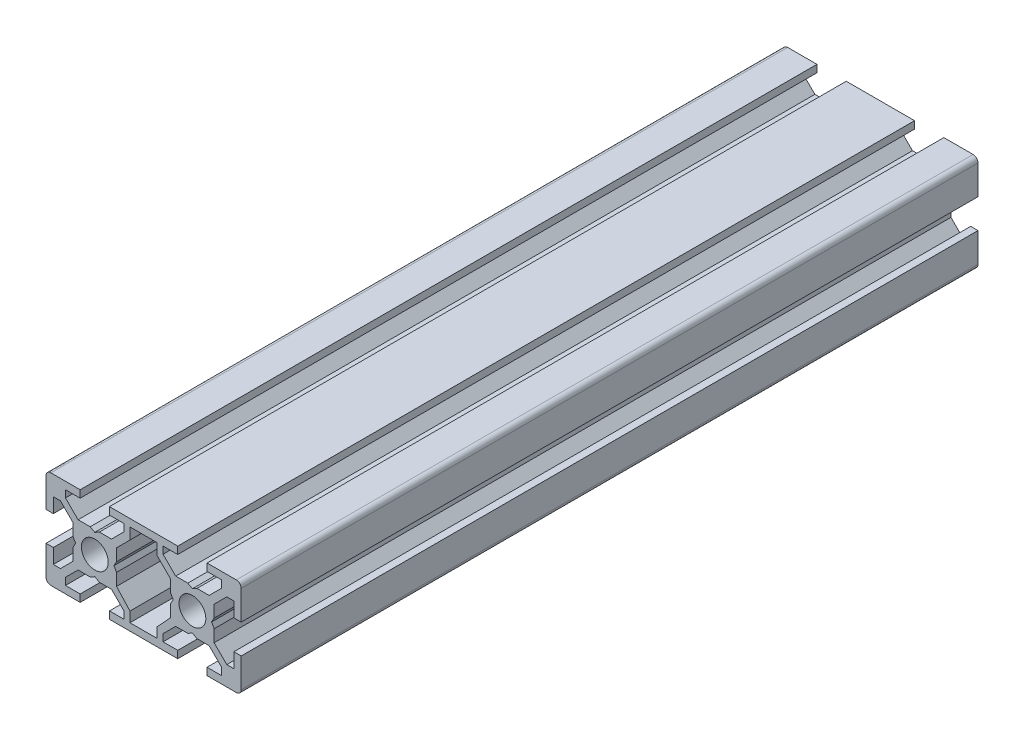
SolidWorks part; units mm, degrees
ref_plane "Front Plane" through (0, 0, 0) normal (0, 0, 1) x (1, 0, 0)
ref_plane "Top Plane" through (0, 0, 0) normal (0, 1, 0) x (1, 0, 0)
ref_plane "Right Plane" through (0, 0, 0) normal (1, 0, 0) x (0, 0, -1)
sketch "Sketch1" plane through (0, 0, 0) normal (0, 0, 1) x (1, 0, 0)
  line L0 (-707.1068, -707.1068) -> (34648.2323, 34648.2323) construction
  line L1 (-3.0018, 10) -> (-10, 10)
  line L2 (0.9376, 4.4579) -> (-0.0011, 3.9339)
  line L3 (3.4252, 4.4579) -> (0.9376, 4.4579)
  line L4 (6.0128, 7.0454) -> (3.4252, 4.4579)
  line L5 (0, -1000) -> (0, 49000) construction
  line L6 (-1000, 0) -> (49000, 0) construction
  line L7 (6.0128, 8.5) -> (6.0128, 7.0454)
  line L8 (3.0018, 8.5) -> (6.0128, 8.5)
  line L9 (3.0018, 10) -> (16.9982, 10)
  line L10 (3.0018, 8.5) -> (3.0018, 10)
  line L11 (-707.1068, 707.1068) -> (34648.2323, -34648.2323) construction
  line L12 (-7.0458, 6.0144) -> (-4.4582, 3.4268)
  line L13 (-8.5008, 6.0144) -> (-7.0458, 6.0144)
  line L14 (-8.5008, 3.0018) -> (-8.5008, 6.0144)
  line L15 (0, -0.0423) -> (0.0002, 2.0704) construction
  line L16 (-10, 3.0018) -> (-10, 10)
  line L17 (-8.5008, 3.0018) -> (-10, 3.0018)
  line L18 (7.2087, -6.4198) -> (7.2087, -8.5)
  line L19 (7.2087, -8.5) -> (12.7913, -8.5)
  line L20 (7.2087, 6.1776) -> (7.2087, 8.5)
  line L21 (7.2087, 8.5) -> (12.7913, 8.5)
  line L22 (7.2087, 6.1776) -> (4.4583, 3.4262)
  line L23 (-3.0018, 8.5) -> (-3.0018, 10)
  line L24 (-3.0018, 8.5) -> (-6.0148, 8.5)
  line L25 (-6.0148, 8.5) -> (-6.0148, 7.0458)
  line L26 (-6.0148, 7.0458) -> (-3.4272, 4.4582)
  line L27 (-3.4272, 4.4582) -> (-0.9396, 4.4582)
  line L28 (-0.9396, 4.4582) -> (-0.0011, 3.9339)
  line L29 (-4.4582, 3.4268) -> (-4.4582, 0.9396)
  line L30 (-4.4582, 0.9396) -> (-3.9347, 0)
  line L31 (4.4575, 0.9396) -> (3.9347, 0)
  line L32 (4.4583, 3.4262) -> (4.4575, 0.9396)
  line L33 (10, -990) -> (10, 49010) construction
  line L34 (19.0624, -4.4579) -> (20.0011, -3.9339)
  line L35 (16.5748, -4.4579) -> (19.0624, -4.4579)
  line L36 (13.9872, -7.0454) -> (16.5748, -4.4579)
  line L37 (-0.9396, -4.4582) -> (-0.0011, -3.9339)
  line L38 (13.9872, -8.5) -> (13.9872, -7.0454)
  line L39 (16.9982, -8.5) -> (13.9872, -8.5)
  line L40 (16.9982, -8.5) -> (16.9982, -10)
  line L41 (24.4575, -0.9396) -> (23.9347, 0)
  line L42 (24.4582, -3.4268) -> (24.4575, -0.9396)
  line L43 (27.0458, -6.0144) -> (24.4582, -3.4268)
  line L44 (28.5008, -6.0144) -> (27.0458, -6.0144)
  line L45 (-3.4272, -4.4582) -> (-0.9396, -4.4582)
  line L46 (-6.0148, -7.0458) -> (-3.4272, -4.4582)
  line L47 (-6.0148, -8.5) -> (-6.0148, -7.0458)
  line L48 (-3.0018, -8.5) -> (-6.0148, -8.5)
  line L49 (-3.0018, -10) -> (-10, -10)
  line L50 (-3.0018, -8.5) -> (-3.0018, -10)
  line L51 (4.4588, -0.9386) -> (3.9347, 0)
  line L52 (4.4583, -3.4262) -> (4.4588, -0.9386)
  line L53 (7.2087, -6.4198) -> (4.4583, -3.4262)
  line L54 (28.5008, -3.0018) -> (28.5008, -6.0144)
  line L55 (30, -3.0018) -> (30, -10)
  line L56 (28.5008, -3.0018) -> (30, -3.0018)
  line L57 (12.7913, -6.4198) -> (15.5417, -3.4262)
  line L58 (-8.5008, -3.0018) -> (-10, -3.0018)
  line L59 (-10, -3.0018) -> (-10, -10)
  line L60 (-8.5008, -3.0018) -> (-8.5008, -6.0144)
  line L61 (-8.5008, -6.0144) -> (-7.0458, -6.0144)
  line L62 (-7.0458, -6.0144) -> (-4.4582, -3.4268)
  line L63 (-4.4582, -3.4268) -> (-4.4575, -0.9396)
  line L64 (-4.4575, -0.9396) -> (-3.9347, 0)
  line L65 (3.0018, -8.5) -> (3.0018, -10)
  line L66 (3.0018, -10) -> (16.9982, -10)
  line L67 (3.0018, -8.5) -> (6.0128, -8.5)
  line L68 (6.0128, -8.5) -> (6.0128, -7.0454)
  line L69 (6.0128, -7.0454) -> (3.4252, -4.4579)
  line L70 (3.4252, -4.4579) -> (0.9376, -4.4579)
  line L71 (0.9376, -4.4579) -> (-0.0011, -3.9339)
  line L72 (15.5417, -3.4262) -> (15.5412, -0.9386)
  line L73 (15.5412, -0.9386) -> (16.0653, 0)
  line L74 (23.0018, -8.5) -> (23.0018, -10)
  line L75 (23.0018, -10) -> (30, -10)
  line L76 (23.0018, -8.5) -> (26.0148, -8.5)
  line L77 (26.0148, -8.5) -> (26.0148, -7.0458)
  line L78 (26.0148, -7.0458) -> (23.4272, -4.4582)
  line L79 (23.4272, -4.4582) -> (20.9396, -4.4582)
  line L80 (20.9396, -4.4582) -> (20.0011, -3.9339)
  line L81 (15.5417, 3.4262) -> (15.5425, 0.9396)
  line L82 (15.5425, 0.9396) -> (16.0653, 0)
  line L83 (24.4582, 0.9396) -> (23.9347, 0)
  line L84 (24.4582, 3.4268) -> (24.4582, 0.9396)
  line L85 (20.9396, 4.4582) -> (20.0011, 3.9339)
  line L86 (23.4272, 4.4582) -> (20.9396, 4.4582)
  line L87 (26.0148, 7.0458) -> (23.4272, 4.4582)
  line L88 (26.0148, 8.5) -> (26.0148, 7.0458)
  line L89 (23.0018, 8.5) -> (26.0148, 8.5)
  line L90 (23.0018, 8.5) -> (23.0018, 10)
  line L91 (12.7913, 6.1776) -> (15.5417, 3.4262)
  line L92 (12.7913, 6.1776) -> (12.7913, 8.5)
  line L93 (12.7913, -6.4198) -> (12.7913, -8.5)
  line L94 (28.5008, 3.0018) -> (30, 3.0018)
  line L95 (30, 3.0018) -> (30, 10)
  line L96 (28.5008, 3.0018) -> (28.5008, 6.0144)
  line L97 (28.5008, 6.0144) -> (27.0458, 6.0144)
  line L98 (27.0458, 6.0144) -> (24.4582, 3.4268)
  line L99 (16.9982, 8.5) -> (16.9982, 10)
  line L100 (16.9982, 8.5) -> (13.9872, 8.5)
  line L101 (13.9872, 8.5) -> (13.9872, 7.0454)
  line L102 (13.9872, 7.0454) -> (16.5748, 4.4579)
  line L103 (16.5748, 4.4579) -> (19.0624, 4.4579)
  line L104 (19.0624, 4.4579) -> (20.0011, 3.9339)
  line L105 (23.0018, 10) -> (30, 10)
  circle A0 centre (0, 0) radius 2.75
  circle A1 centre (20, 0) radius 2.75
  point P76 (10, -10)
  point P79 (10, -10)
  point P88 (10, -3.0018)
  point P111 (10, 8.5)
  point P112 (10, -8.5)
  point P114 (10, 3.0018)
  point P120 (10, 10)
  point P121 (10, 10)
extrude "Boss-Extrude1" add sketch "Sketch1" along normal blind 151
fillet "Fillet2" radius 1 1 edges at (-10, -10, 75.5)
fillet "Fillet4" radius 1 1 edges at (-10, 10, 75.5)
fillet "Fillet5" radius 1 1 edges at (30, 10, 75.5)
fillet "Fillet6" radius 1 1 edges at (30, -10, 75.5)
